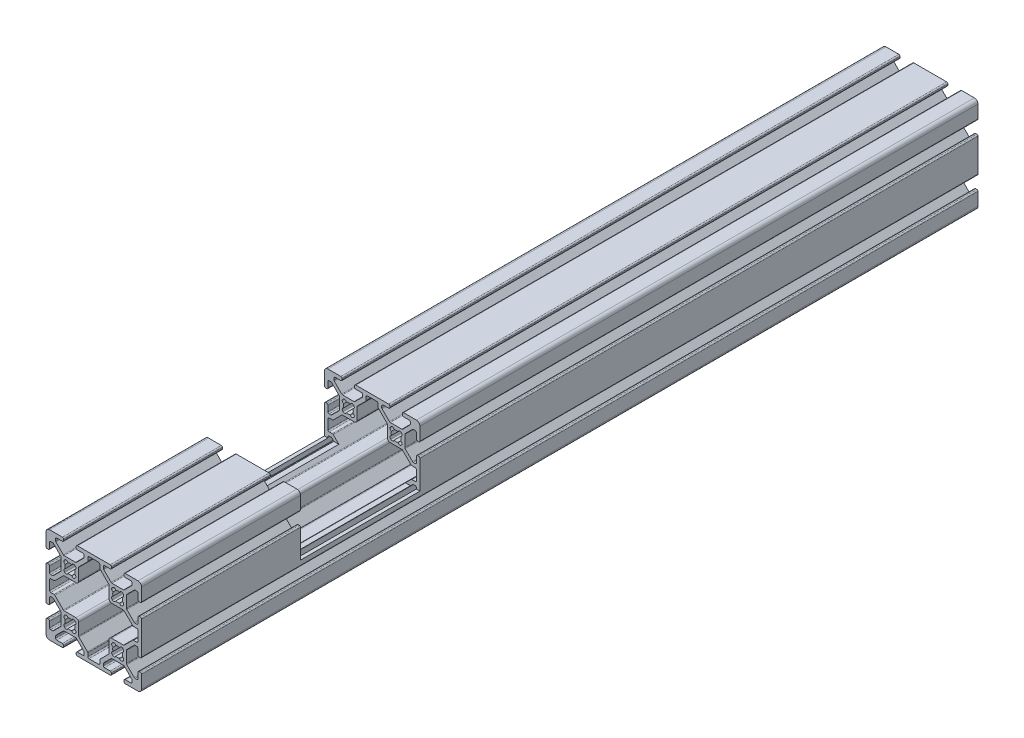
SolidWorks part; units mm, degrees
material "6105-T5 Aluminum"
ref_plane "Front Plane" through (0, 0, 0) normal (0, 0, 1) x (1, 0, 0)
ref_plane "Top Plane" through (0, 0, 0) normal (0, 1, 0) x (1, 0, 0)
ref_plane "Right Plane" through (0, 0, 0) normal (1, 0, 0) x (0, 0, -1)
sketch "Sketch1" plane through (0, 0, 0) normal (0, 0, 1) x (1, 0, 0)
  line L0 (-2.1249, 17.6955) -> (-2.3045, 17.8751)
  line L1 (-2.3045, 22.1249) -> (-2.1249, 22.3045)
  line L2 (2.1249, 22.3045) -> (2.3045, 22.1249)
  line L3 (2.3045, 17.8751) -> (2.1249, 17.6955)
  line L4 (-22.1249, 17.6955) -> (-22.3045, 17.8751)
  line L5 (-22.3045, 22.1249) -> (-22.1249, 22.3045)
  line L6 (-17.8751, 22.3045) -> (-17.6955, 22.1249)
  line L7 (-17.6955, 17.8751) -> (-17.8751, 17.6955)
  line L8 (-2.1249, -2.3045) -> (-2.3045, -2.1249)
  line L9 (-2.3045, 2.1249) -> (-2.1249, 2.3045)
  line L10 (2.1249, 2.3045) -> (2.3045, 2.1249)
  line L11 (2.3045, -2.1249) -> (2.1249, -2.3045)
  line L12 (-12.505, -7.992) -> (-12.505, -6.6448)
  line L13 (-12.6538, -6.2856) -> (-16.1962, -2.7431)
  line L14 (-16.345, -2.3839) -> (-16.345, 2.512)
  line L15 (-17.488, 3.655) -> (-22.3839, 3.655)
  line L16 (-22.7431, 3.8038) -> (-26.2856, 7.3462)
  line L17 (-26.6448, 7.495) -> (-27.992, 7.495)
  line L18 (-28.5, 8.003) -> (-28.5, 11.997)
  line L19 (-27.992, 12.505) -> (-26.6448, 12.505)
  line L20 (-26.2856, 12.6538) -> (-22.7431, 16.1962)
  line L21 (-22.3839, 16.345) -> (-17.488, 16.345)
  line L22 (-16.345, 17.488) -> (-16.345, 22.3839)
  line L23 (-16.1962, 22.7431) -> (-12.6538, 26.2856)
  line L24 (-12.505, 26.6448) -> (-12.505, 27.992)
  line L25 (-11.997, 28.5) -> (-8.003, 28.5)
  line L26 (-7.495, 27.992) -> (-7.495, 26.6448)
  line L27 (-7.3462, 26.2856) -> (-3.8038, 22.7431)
  line L28 (-3.655, 22.3839) -> (-3.655, 17.488)
  line L29 (-2.512, 16.345) -> (2.3839, 16.345)
  line L30 (2.7431, 16.1962) -> (6.2856, 12.6538)
  line L31 (6.6448, 12.505) -> (7.992, 12.505)
  line L32 (8.5, 11.997) -> (8.5, 8.003)
  line L33 (7.992, 7.495) -> (6.6448, 7.495)
  line L34 (6.2856, 7.3462) -> (2.7431, 3.8038)
  line L35 (2.3839, 3.655) -> (-2.512, 3.655)
  line L36 (-3.655, 2.512) -> (-3.655, -2.3839)
  line L37 (-3.8038, -2.7431) -> (-7.3462, -6.2856)
  line L38 (-7.495, -6.6448) -> (-7.495, -7.992)
  line L39 (-8.003, -8.5) -> (-11.997, -8.5)
  line L40 (-22.1249, -2.3045) -> (-22.3045, -2.1249)
  line L41 (-22.3045, 2.1249) -> (-22.1249, 2.3045)
  line L42 (-17.8751, 2.3045) -> (-17.6955, 2.1249)
  line L43 (-17.6955, -2.1249) -> (-17.8751, -2.3045)
  line L44 (-22.3839, -3.655) -> (-17.6161, -3.655)
  line L45 (-17.2569, -3.8038) -> (-14.1538, -6.9069)
  line L46 (-14.005, -7.2661) -> (-14.005, -7.992)
  line L47 (-14.513, -8.5) -> (-16.862, -8.5)
  line L48 (-17.37, -9.008) -> (-17.37, -9.492)
  line L49 (-16.862, -10) -> (-3.138, -10)
  line L50 (-2.63, -9.492) -> (-2.63, -9.008)
  line L51 (-3.138, -8.5) -> (-5.487, -8.5)
  line L52 (-5.995, -7.992) -> (-5.995, -7.2661)
  line L53 (-5.8462, -6.9069) -> (-2.7431, -3.8038)
  line L54 (-2.3839, -3.655) -> (2.3839, -3.655)
  line L55 (2.7431, -3.8038) -> (5.8462, -6.9069)
  line L56 (5.995, -7.2661) -> (5.995, -7.992)
  line L57 (5.487, -8.5) -> (3.138, -8.5)
  line L58 (2.63, -9.008) -> (2.63, -9.492)
  line L59 (3.138, -10) -> (8.5, -10)
  line L60 (10, -8.5) -> (10, -3.138)
  line L61 (9.492, -2.63) -> (9.008, -2.63)
  line L62 (8.5, -3.138) -> (8.5, -5.487)
  line L63 (7.992, -5.995) -> (7.2661, -5.995)
  line L64 (6.9069, -5.8462) -> (3.8038, -2.7431)
  line L65 (3.655, -2.3839) -> (3.655, 2.3839)
  line L66 (3.8038, 2.7431) -> (6.9069, 5.8462)
  line L67 (7.2661, 5.995) -> (7.992, 5.995)
  line L68 (8.5, 5.487) -> (8.5, 3.138)
  line L69 (9.008, 2.63) -> (9.492, 2.63)
  line L70 (10, 3.138) -> (10, 16.862)
  line L71 (9.492, 17.37) -> (9.008, 17.37)
  line L72 (8.5, 16.862) -> (8.5, 14.513)
  line L73 (7.992, 14.005) -> (7.2661, 14.005)
  line L74 (6.9069, 14.1538) -> (3.8038, 17.2569)
  line L75 (3.655, 17.6161) -> (3.655, 22.3839)
  line L76 (3.8038, 22.7431) -> (6.9069, 25.8462)
  line L77 (7.2661, 25.995) -> (7.992, 25.995)
  line L78 (8.5, 25.487) -> (8.5, 23.138)
  line L79 (9.008, 22.63) -> (9.492, 22.63)
  line L80 (10, 23.138) -> (10, 28.5)
  line L81 (8.5, 30) -> (3.138, 30)
  line L82 (2.63, 29.492) -> (2.63, 29.008)
  line L83 (3.138, 28.5) -> (5.487, 28.5)
  line L84 (5.995, 27.992) -> (5.995, 27.2661)
  line L85 (5.8462, 26.9069) -> (2.7431, 23.8038)
  line L86 (2.3839, 23.655) -> (-2.3839, 23.655)
  line L87 (-2.7431, 23.8038) -> (-5.8462, 26.9069)
  line L88 (-5.995, 27.2661) -> (-5.995, 27.992)
  line L89 (-5.487, 28.5) -> (-3.138, 28.5)
  line L90 (-2.63, 29.008) -> (-2.63, 29.492)
  line L91 (-3.138, 30) -> (-16.862, 30)
  line L92 (-17.37, 29.492) -> (-17.37, 29.008)
  line L93 (-16.862, 28.5) -> (-14.513, 28.5)
  line L94 (-14.005, 27.992) -> (-14.005, 27.2661)
  line L95 (-14.1538, 26.9069) -> (-17.2569, 23.8038)
  line L96 (-17.6161, 23.655) -> (-22.3839, 23.655)
  line L97 (-22.7431, 23.8038) -> (-25.8462, 26.9069)
  line L98 (-25.995, 27.2661) -> (-25.995, 27.992)
  line L99 (-25.487, 28.5) -> (-23.138, 28.5)
  line L100 (-22.63, 29.008) -> (-22.63, 29.492)
  line L101 (-23.138, 30) -> (-28.5, 30)
  line L102 (-30, 28.5) -> (-30, 23.138)
  line L103 (-29.492, 22.63) -> (-29.008, 22.63)
  line L104 (-28.5, 23.138) -> (-28.5, 25.487)
  line L105 (-27.992, 25.995) -> (-27.2661, 25.995)
  line L106 (-26.9069, 25.8462) -> (-23.8038, 22.7431)
  line L107 (-23.655, 22.3839) -> (-23.655, 17.6161)
  line L108 (-23.8038, 17.2569) -> (-26.9069, 14.1538)
  line L109 (-27.2661, 14.005) -> (-27.992, 14.005)
  line L110 (-28.5, 14.513) -> (-28.5, 16.862)
  line L111 (-29.008, 17.37) -> (-29.492, 17.37)
  line L112 (-30, 16.862) -> (-30, 3.138)
  line L113 (-29.492, 2.63) -> (-29.008, 2.63)
  line L114 (-28.5, 3.138) -> (-28.5, 5.487)
  line L115 (-27.992, 5.995) -> (-27.2661, 5.995)
  line L116 (-26.9069, 5.8462) -> (-23.8038, 2.7431)
  line L117 (-23.655, 2.3839) -> (-23.655, -2.3839)
  line L118 (-23.8038, -2.7431) -> (-26.9069, -5.8462)
  line L119 (-27.2661, -5.995) -> (-27.992, -5.995)
  line L120 (-28.5, -5.487) -> (-28.5, -3.138)
  line L121 (-29.008, -2.63) -> (-29.492, -2.63)
  line L122 (-30, -3.138) -> (-30, -8.5)
  line L123 (-28.5, -10) -> (-23.138, -10)
  line L124 (-22.63, -9.492) -> (-22.63, -9.008)
  line L125 (-23.138, -8.5) -> (-25.487, -8.5)
  line L126 (-25.995, -7.992) -> (-25.995, -7.2661)
  line L127 (-25.8462, -6.9069) -> (-22.7431, -3.8038)
  arc A0 (-1.9351, 19.196) -> (-2.3045, 17.8751) centre (-1.748, 18.4316) ccw
  arc A1 (-1.9351, 20.804) -> (-1.9351, 19.196) centre (0, 20) ccw
  arc A2 (-2.3045, 22.1249) -> (-1.9351, 20.804) centre (-1.748, 21.5684) ccw
  arc A3 (-0.804, 21.9351) -> (-2.1249, 22.3045) centre (-1.5684, 21.748) ccw
  arc A4 (0.804, 21.9351) -> (-0.804, 21.9351) centre (0, 20) ccw
  arc A5 (2.1249, 22.3045) -> (0.804, 21.9351) centre (1.5684, 21.748) ccw
  arc A6 (1.9351, 20.804) -> (2.3045, 22.1249) centre (1.748, 21.5684) ccw
  arc A7 (1.9351, 19.196) -> (1.9351, 20.804) centre (0, 20) ccw
  arc A8 (2.3045, 17.8751) -> (1.9351, 19.196) centre (1.748, 18.4316) ccw
  arc A9 (0.804, 18.0649) -> (2.1249, 17.6955) centre (1.5684, 18.252) ccw
  arc A10 (-0.804, 18.0649) -> (0.804, 18.0649) centre (0, 20) ccw
  arc A11 (-2.1249, 17.6955) -> (-0.804, 18.0649) centre (-1.5684, 18.252) ccw
  arc A12 (-21.9351, 19.196) -> (-22.3045, 17.8751) centre (-21.748, 18.4316) ccw
  arc A13 (-21.9351, 20.804) -> (-21.9351, 19.196) centre (-20, 20) ccw
  arc A14 (-22.3045, 22.1249) -> (-21.9351, 20.804) centre (-21.748, 21.5684) ccw
  arc A15 (-20.804, 21.9351) -> (-22.1249, 22.3045) centre (-21.5684, 21.748) ccw
  arc A16 (-19.196, 21.9351) -> (-20.804, 21.9351) centre (-20, 20) ccw
  arc A17 (-17.8751, 22.3045) -> (-19.196, 21.9351) centre (-18.4316, 21.748) ccw
  arc A18 (-18.0649, 20.804) -> (-17.6955, 22.1249) centre (-18.252, 21.5684) ccw
  arc A19 (-18.0649, 19.196) -> (-18.0649, 20.804) centre (-20, 20) ccw
  arc A20 (-17.6955, 17.8751) -> (-18.0649, 19.196) centre (-18.252, 18.4316) ccw
  arc A21 (-19.196, 18.0649) -> (-17.8751, 17.6955) centre (-18.4316, 18.252) ccw
  arc A22 (-20.804, 18.0649) -> (-19.196, 18.0649) centre (-20, 20) ccw
  arc A23 (-22.1249, 17.6955) -> (-20.804, 18.0649) centre (-21.5684, 18.252) ccw
  arc A24 (-1.9351, -0.804) -> (-2.3045, -2.1249) centre (-1.748, -1.5684) ccw
  arc A25 (-1.9351, 0.804) -> (-1.9351, -0.804) centre (0, 0) ccw
  arc A26 (-2.3045, 2.1249) -> (-1.9351, 0.804) centre (-1.748, 1.5684) ccw
  arc A27 (-0.804, 1.9351) -> (-2.1249, 2.3045) centre (-1.5684, 1.748) ccw
  arc A28 (0.804, 1.9351) -> (-0.804, 1.9351) centre (0, 0) ccw
  arc A29 (2.1249, 2.3045) -> (0.804, 1.9351) centre (1.5684, 1.748) ccw
  arc A30 (1.9351, 0.804) -> (2.3045, 2.1249) centre (1.748, 1.5684) ccw
  arc A31 (1.9351, -0.804) -> (1.9351, 0.804) centre (0, 0) ccw
  arc A32 (2.3045, -2.1249) -> (1.9351, -0.804) centre (1.748, -1.5684) ccw
  arc A33 (0.804, -1.9351) -> (2.1249, -2.3045) centre (1.5684, -1.748) ccw
  arc A34 (-0.804, -1.9351) -> (0.804, -1.9351) centre (0, 0) ccw
  arc A35 (-2.1249, -2.3045) -> (-0.804, -1.9351) centre (-1.5684, -1.748) ccw
  arc A36 (-12.505, -7.992) -> (-11.997, -8.5) centre (-11.997, -7.992) ccw
  arc A37 (-12.505, -6.6448) -> (-12.6538, -6.2856) centre (-13.013, -6.6448) ccw
  arc A38 (-16.345, -2.3839) -> (-16.1962, -2.7431) centre (-15.837, -2.3839) ccw
  arc A39 (-16.345, 2.512) -> (-17.488, 3.655) centre (-17.488, 2.512) ccw
  arc A40 (-22.7431, 3.8038) -> (-22.3839, 3.655) centre (-22.3839, 4.163) ccw
  arc A41 (-26.2856, 7.3462) -> (-26.6448, 7.495) centre (-26.6448, 6.987) ccw
  arc A42 (-28.5, 8.003) -> (-27.992, 7.495) centre (-27.992, 8.003) ccw
  arc A43 (-27.992, 12.505) -> (-28.5, 11.997) centre (-27.992, 11.997) ccw
  arc A44 (-26.6448, 12.505) -> (-26.2856, 12.6538) centre (-26.6448, 13.013) ccw
  arc A45 (-22.3839, 16.345) -> (-22.7431, 16.1962) centre (-22.3839, 15.837) ccw
  arc A46 (-17.488, 16.345) -> (-16.345, 17.488) centre (-17.488, 17.488) ccw
  arc A47 (-16.1962, 22.7431) -> (-16.345, 22.3839) centre (-15.837, 22.3839) ccw
  arc A48 (-12.6538, 26.2856) -> (-12.505, 26.6448) centre (-13.013, 26.6448) ccw
  arc A49 (-11.997, 28.5) -> (-12.505, 27.992) centre (-11.997, 27.992) ccw
  arc A50 (-7.495, 27.992) -> (-8.003, 28.5) centre (-8.003, 27.992) ccw
  arc A51 (-7.495, 26.6448) -> (-7.3462, 26.2856) centre (-6.987, 26.6448) ccw
  arc A52 (-3.655, 22.3839) -> (-3.8038, 22.7431) centre (-4.163, 22.3839) ccw
  arc A53 (-3.655, 17.488) -> (-2.512, 16.345) centre (-2.512, 17.488) ccw
  arc A54 (2.7431, 16.1962) -> (2.3839, 16.345) centre (2.3839, 15.837) ccw
  arc A55 (6.2856, 12.6538) -> (6.6448, 12.505) centre (6.6448, 13.013) ccw
  arc A56 (8.5, 11.997) -> (7.992, 12.505) centre (7.992, 11.997) ccw
  arc A57 (7.992, 7.495) -> (8.5, 8.003) centre (7.992, 8.003) ccw
  arc A58 (6.6448, 7.495) -> (6.2856, 7.3462) centre (6.6448, 6.987) ccw
  arc A59 (2.3839, 3.655) -> (2.7431, 3.8038) centre (2.3839, 4.163) ccw
  arc A60 (-2.512, 3.655) -> (-3.655, 2.512) centre (-2.512, 2.512) ccw
  arc A61 (-3.8038, -2.7431) -> (-3.655, -2.3839) centre (-4.163, -2.3839) ccw
  arc A62 (-7.3462, -6.2856) -> (-7.495, -6.6448) centre (-6.987, -6.6448) ccw
  arc A63 (-8.003, -8.5) -> (-7.495, -7.992) centre (-8.003, -7.992) ccw
  arc A64 (-21.9351, -0.804) -> (-22.3045, -2.1249) centre (-21.748, -1.5684) ccw
  arc A65 (-21.9351, 0.804) -> (-21.9351, -0.804) centre (-20, 0) ccw
  arc A66 (-22.3045, 2.1249) -> (-21.9351, 0.804) centre (-21.748, 1.5684) ccw
  arc A67 (-20.804, 1.9351) -> (-22.1249, 2.3045) centre (-21.5684, 1.748) ccw
  arc A68 (-19.196, 1.9351) -> (-20.804, 1.9351) centre (-20, 0) ccw
  arc A69 (-17.8751, 2.3045) -> (-19.196, 1.9351) centre (-18.4316, 1.748) ccw
  arc A70 (-18.0649, 0.804) -> (-17.6955, 2.1249) centre (-18.252, 1.5684) ccw
  arc A71 (-18.0649, -0.804) -> (-18.0649, 0.804) centre (-20, 0) ccw
  arc A72 (-17.6955, -2.1249) -> (-18.0649, -0.804) centre (-18.252, -1.5684) ccw
  arc A73 (-19.196, -1.9351) -> (-17.8751, -2.3045) centre (-18.4316, -1.748) ccw
  arc A74 (-20.804, -1.9351) -> (-19.196, -1.9351) centre (-20, 0) ccw
  arc A75 (-22.1249, -2.3045) -> (-20.804, -1.9351) centre (-21.5684, -1.748) ccw
  arc A76 (-22.3839, -3.655) -> (-22.7431, -3.8038) centre (-22.3839, -4.163) ccw
  arc A77 (-17.2569, -3.8038) -> (-17.6161, -3.655) centre (-17.6161, -4.163) ccw
  arc A78 (-14.005, -7.2661) -> (-14.1538, -6.9069) centre (-14.513, -7.2661) ccw
  arc A79 (-14.513, -8.5) -> (-14.005, -7.992) centre (-14.513, -7.992) ccw
  arc A80 (-16.862, -8.5) -> (-17.37, -9.008) centre (-16.862, -9.008) ccw
  arc A81 (-17.37, -9.492) -> (-16.862, -10) centre (-16.862, -9.492) ccw
  arc A82 (-3.138, -10) -> (-2.63, -9.492) centre (-3.138, -9.492) ccw
  arc A83 (-2.63, -9.008) -> (-3.138, -8.5) centre (-3.138, -9.008) ccw
  arc A84 (-5.995, -7.992) -> (-5.487, -8.5) centre (-5.487, -7.992) ccw
  arc A85 (-5.8462, -6.9069) -> (-5.995, -7.2661) centre (-5.487, -7.2661) ccw
  arc A86 (-2.3839, -3.655) -> (-2.7431, -3.8038) centre (-2.3839, -4.163) ccw
  arc A87 (2.7431, -3.8038) -> (2.3839, -3.655) centre (2.3839, -4.163) ccw
  arc A88 (5.995, -7.2661) -> (5.8462, -6.9069) centre (5.487, -7.2661) ccw
  arc A89 (5.487, -8.5) -> (5.995, -7.992) centre (5.487, -7.992) ccw
  arc A90 (3.138, -8.5) -> (2.63, -9.008) centre (3.138, -9.008) ccw
  arc A91 (2.63, -9.492) -> (3.138, -10) centre (3.138, -9.492) ccw
  arc A92 (8.5, -10) -> (10, -8.5) centre (8.5, -8.5) ccw
  arc A93 (10, -3.138) -> (9.492, -2.63) centre (9.492, -3.138) ccw
  arc A94 (9.008, -2.63) -> (8.5, -3.138) centre (9.008, -3.138) ccw
  arc A95 (7.992, -5.995) -> (8.5, -5.487) centre (7.992, -5.487) ccw
  arc A96 (6.9069, -5.8462) -> (7.2661, -5.995) centre (7.2661, -5.487) ccw
  arc A97 (3.655, -2.3839) -> (3.8038, -2.7431) centre (4.163, -2.3839) ccw
  arc A98 (3.8038, 2.7431) -> (3.655, 2.3839) centre (4.163, 2.3839) ccw
  arc A99 (7.2661, 5.995) -> (6.9069, 5.8462) centre (7.2661, 5.487) ccw
  arc A100 (8.5, 5.487) -> (7.992, 5.995) centre (7.992, 5.487) ccw
  arc A101 (8.5, 3.138) -> (9.008, 2.63) centre (9.008, 3.138) ccw
  arc A102 (9.492, 2.63) -> (10, 3.138) centre (9.492, 3.138) ccw
  arc A103 (10, 16.862) -> (9.492, 17.37) centre (9.492, 16.862) ccw
  arc A104 (9.008, 17.37) -> (8.5, 16.862) centre (9.008, 16.862) ccw
  arc A105 (7.992, 14.005) -> (8.5, 14.513) centre (7.992, 14.513) ccw
  arc A106 (6.9069, 14.1538) -> (7.2661, 14.005) centre (7.2661, 14.513) ccw
  arc A107 (3.655, 17.6161) -> (3.8038, 17.2569) centre (4.163, 17.6161) ccw
  arc A108 (3.8038, 22.7431) -> (3.655, 22.3839) centre (4.163, 22.3839) ccw
  arc A109 (7.2661, 25.995) -> (6.9069, 25.8462) centre (7.2661, 25.487) ccw
  arc A110 (8.5, 25.487) -> (7.992, 25.995) centre (7.992, 25.487) ccw
  arc A111 (8.5, 23.138) -> (9.008, 22.63) centre (9.008, 23.138) ccw
  arc A112 (9.492, 22.63) -> (10, 23.138) centre (9.492, 23.138) ccw
  arc A113 (10, 28.5) -> (8.5, 30) centre (8.5, 28.5) ccw
  arc A114 (3.138, 30) -> (2.63, 29.492) centre (3.138, 29.492) ccw
  arc A115 (2.63, 29.008) -> (3.138, 28.5) centre (3.138, 29.008) ccw
  arc A116 (5.995, 27.992) -> (5.487, 28.5) centre (5.487, 27.992) ccw
  arc A117 (5.8462, 26.9069) -> (5.995, 27.2661) centre (5.487, 27.2661) ccw
  arc A118 (2.3839, 23.655) -> (2.7431, 23.8038) centre (2.3839, 24.163) ccw
  arc A119 (-2.7431, 23.8038) -> (-2.3839, 23.655) centre (-2.3839, 24.163) ccw
  arc A120 (-5.995, 27.2661) -> (-5.8462, 26.9069) centre (-5.487, 27.2661) ccw
  arc A121 (-5.487, 28.5) -> (-5.995, 27.992) centre (-5.487, 27.992) ccw
  arc A122 (-3.138, 28.5) -> (-2.63, 29.008) centre (-3.138, 29.008) ccw
  arc A123 (-2.63, 29.492) -> (-3.138, 30) centre (-3.138, 29.492) ccw
  arc A124 (-16.862, 30) -> (-17.37, 29.492) centre (-16.862, 29.492) ccw
  arc A125 (-17.37, 29.008) -> (-16.862, 28.5) centre (-16.862, 29.008) ccw
  arc A126 (-14.005, 27.992) -> (-14.513, 28.5) centre (-14.513, 27.992) ccw
  arc A127 (-14.1538, 26.9069) -> (-14.005, 27.2661) centre (-14.513, 27.2661) ccw
  arc A128 (-17.6161, 23.655) -> (-17.2569, 23.8038) centre (-17.6161, 24.163) ccw
  arc A129 (-22.7431, 23.8038) -> (-22.3839, 23.655) centre (-22.3839, 24.163) ccw
  arc A130 (-25.995, 27.2661) -> (-25.8462, 26.9069) centre (-25.487, 27.2661) ccw
  arc A131 (-25.487, 28.5) -> (-25.995, 27.992) centre (-25.487, 27.992) ccw
  arc A132 (-23.138, 28.5) -> (-22.63, 29.008) centre (-23.138, 29.008) ccw
  arc A133 (-22.63, 29.492) -> (-23.138, 30) centre (-23.138, 29.492) ccw
  arc A134 (-28.5, 30) -> (-30, 28.5) centre (-28.5, 28.5) ccw
  arc A135 (-30, 23.138) -> (-29.492, 22.63) centre (-29.492, 23.138) ccw
  arc A136 (-29.008, 22.63) -> (-28.5, 23.138) centre (-29.008, 23.138) ccw
  arc A137 (-27.992, 25.995) -> (-28.5, 25.487) centre (-27.992, 25.487) ccw
  arc A138 (-26.9069, 25.8462) -> (-27.2661, 25.995) centre (-27.2661, 25.487) ccw
  arc A139 (-23.655, 22.3839) -> (-23.8038, 22.7431) centre (-24.163, 22.3839) ccw
  arc A140 (-23.8038, 17.2569) -> (-23.655, 17.6161) centre (-24.163, 17.6161) ccw
  arc A141 (-27.2661, 14.005) -> (-26.9069, 14.1538) centre (-27.2661, 14.513) ccw
  arc A142 (-28.5, 14.513) -> (-27.992, 14.005) centre (-27.992, 14.513) ccw
  arc A143 (-28.5, 16.862) -> (-29.008, 17.37) centre (-29.008, 16.862) ccw
  arc A144 (-29.492, 17.37) -> (-30, 16.862) centre (-29.492, 16.862) ccw
  arc A145 (-30, 3.138) -> (-29.492, 2.63) centre (-29.492, 3.138) ccw
  arc A146 (-29.008, 2.63) -> (-28.5, 3.138) centre (-29.008, 3.138) ccw
  arc A147 (-27.992, 5.995) -> (-28.5, 5.487) centre (-27.992, 5.487) ccw
  arc A148 (-26.9069, 5.8462) -> (-27.2661, 5.995) centre (-27.2661, 5.487) ccw
  arc A149 (-23.655, 2.3839) -> (-23.8038, 2.7431) centre (-24.163, 2.3839) ccw
  arc A150 (-23.8038, -2.7431) -> (-23.655, -2.3839) centre (-24.163, -2.3839) ccw
  arc A151 (-27.2661, -5.995) -> (-26.9069, -5.8462) centre (-27.2661, -5.487) ccw
  arc A152 (-28.5, -5.487) -> (-27.992, -5.995) centre (-27.992, -5.487) ccw
  arc A153 (-28.5, -3.138) -> (-29.008, -2.63) centre (-29.008, -3.138) ccw
  arc A154 (-29.492, -2.63) -> (-30, -3.138) centre (-29.492, -3.138) ccw
  arc A155 (-30, -8.5) -> (-28.5, -10) centre (-28.5, -8.5) ccw
  arc A156 (-23.138, -10) -> (-22.63, -9.492) centre (-23.138, -9.492) ccw
  arc A157 (-22.63, -9.008) -> (-23.138, -8.5) centre (-23.138, -9.008) ccw
  arc A158 (-25.995, -7.992) -> (-25.487, -8.5) centre (-25.487, -7.992) ccw
  arc A159 (-25.8462, -6.9069) -> (-25.995, -7.2661) centre (-25.487, -7.2661) ccw
extrude "Extrude1" add sketch "Sketch1" against normal blind 350
sketch "Sketch2" plane through (10, 0, 0) normal (1, 0, 0) x (0, 0, -1)
  line L0 (350, 30) -> (0, 30) construction
  line L1 (66.4865, 5) -> (116.4865, 5)
  line L2 (66.4865, 5) -> (66.4865, 30)
  line L3 (66.4865, 30) -> (116.4865, 30)
  line L4 (116.4865, 5) -> (116.4865, 30)
extrude "Cut-Extrude2" cut sketch "Sketch2" against normal blind 62
